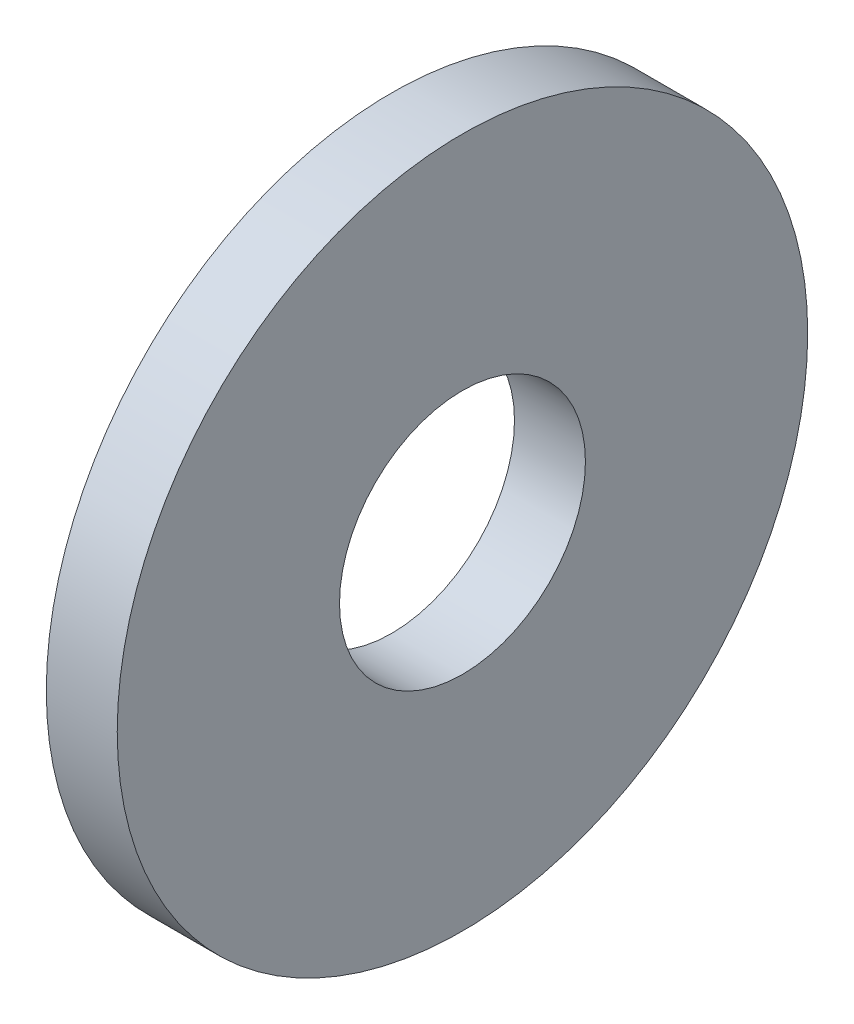
SolidWorks part; units mm, degrees
ref_plane "Front Plane" through (0, 0, 0) normal (0, 0, 1) x (1, 0, 0)
ref_plane "Top Plane" through (0, 0, 0) normal (0, 1, 0) x (1, 0, 0)
ref_plane "Right Plane" through (0, 0, 0) normal (1, 0, 0) x (0, 0, -1)
sketch "Sketch1" plane through (0, 0, 0) normal (1, 0, 0) x (0, 0, -1)
  circle A0 centre (0, 0) radius 1.9812
  circle A1 centre (0, 0) radius 5.5626
  dimension "OD" = 3.9624
  dimension "ID" = 11.1252
extrude "Boss-Extrude1" add sketch "Sketch1" along normal blind 1.143
